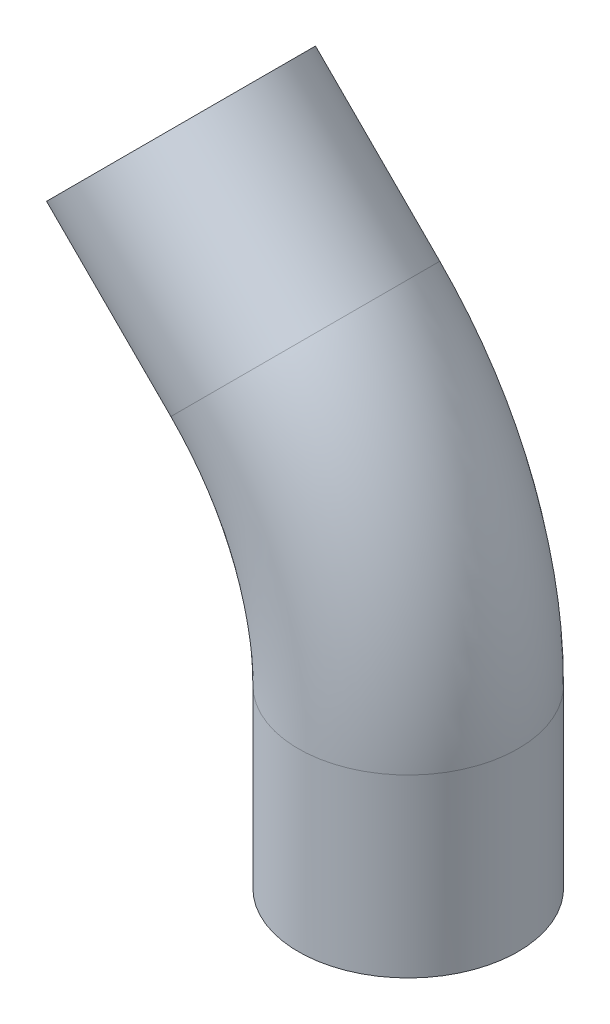
SolidWorks part; units mm, degrees
ref_plane "Front Plane" through (0, 0, 0) normal (0, 0, 1) x (1, 0, 0)
ref_plane "Top Plane" through (0, 0, 0) normal (0, 1, 0) x (1, 0, 0)
ref_plane "Right Plane" through (0, 0, 0) normal (1, 0, 0) x (0, 0, -1)
sketch "Sketch1" plane through (0, 0, 0) normal (0, 0, 1) x (1, 0, 0)
  line L1 (0, 0) -> (-80, 0) construction
  line L2 (-80, 0) -> (-23.4315, 56.5685) construction
  line L4 (-23.4315, 56.5685) -> (-51.7157, 84.8528)
  line L5 (0, 0) -> (0, -40)
  arc A0 (0, 0) -> (-23.4315, 56.5685) centre (-80, 0) ccw
  dimension "D3" = 80
  dimension "D1" = 40
  dimension "D2" = 40
  dimension "D4" = 45
ref_plane "Plane1" through (0, -40, 0) normal (0, -1, 0) x (-1, 0, 0)
sketch "Sketch2" plane through (0, -40, 0) normal (0, -1, 0) x (-1, 0, 0)
  circle A0 centre (0, 0) radius 25
  dimension "D1" = 50
sweep "Sweep1" add profiles "Sketch2" path "Sketch1"
shell "Shell1" thickness 5
